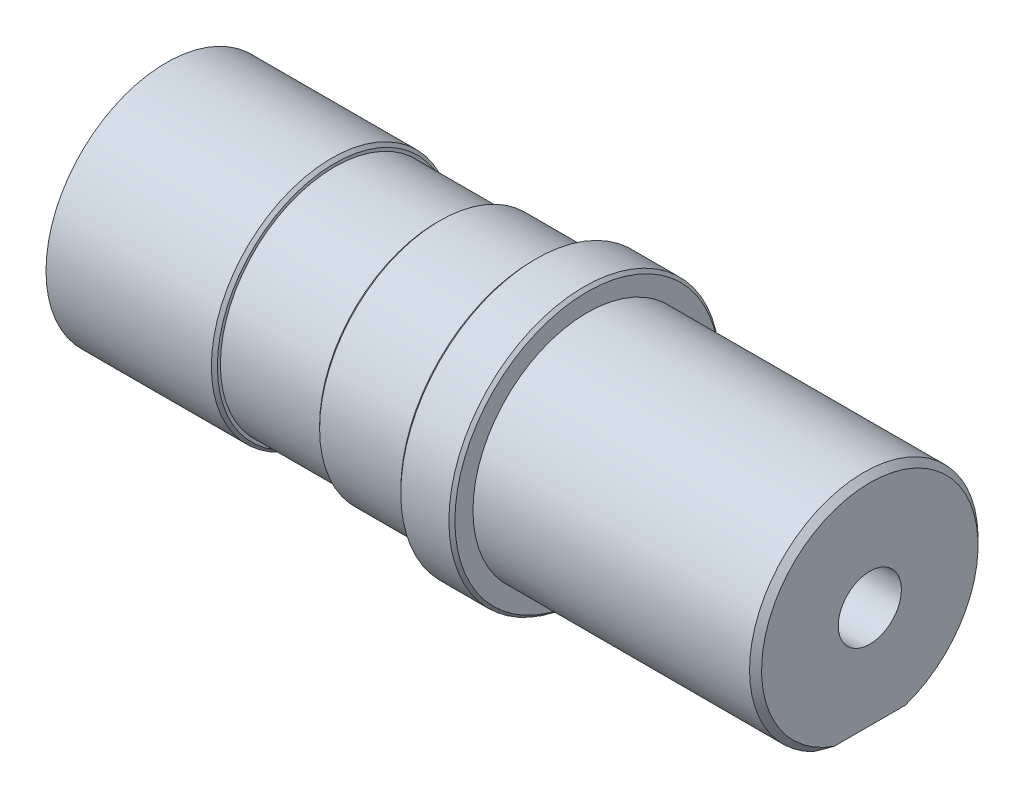
SolidWorks part; units mm, degrees
ref_plane "前视基准面" through (0, 0, 0) normal (0, 0, 1) x (1, 0, 0)
ref_plane "上视基准面" through (0, 0, 0) normal (0, 1, 0) x (1, 0, 0)
ref_plane "右视基准面" through (0, 0, 0) normal (1, 0, 0) x (0, 0, -1)
sketch "草图1" plane through (0, 0, 0) normal (0, 0, 1) x (1, 0, 0)
  line L1 (2043.9736, 794.7901) -> (2043.9736, 776.7901)
  line L2 (1954.9736, 796.2901) -> (1954.9736, 795.7901)
  line L3 (1971.9736, 796.2901) -> (1972.4736, 796.7901)
  line L4 (1996.4736, 799.2901) -> (1988.4736, 799.2901)
  line L5 (1987.9736, 796.7901) -> (1972.4736, 796.7901)
  line L6 (1954.4736, 796.7901) -> (1926.9736, 796.7901)
  line L7 (2042.9736, 795.7901) -> (1996.9736, 795.7901)
  line L8 (1971.9736, 795.7901) -> (1954.9736, 795.7901)
  line L9 (1996.9736, 798.7901) -> (1996.9736, 795.7901)
  line L10 (1971.9736, 796.2901) -> (1971.9736, 795.7901)
  line L11 (1987.9736, 798.7901) -> (1988.4736, 799.2901)
  line L12 (1987.9736, 798.7901) -> (1987.9736, 796.7901)
  line L14 (1954.9736, 796.2901) -> (1954.4736, 796.7901)
  line L16 (1926.9736, 776.7901) -> (2043.9736, 776.7901)
  line L17 (1926.9736, 776.7901) -> (2039.9736, 776.7901) construction
  line L18 (1926.9736, 776.7901) -> (1926.9736, 796.7901)
  line L23 (2042.9736, 795.7901) -> (2043.9736, 794.7901)
  line L26 (2046.9736, 776.7901) -> (2063.4038, 776.7901) construction
  line L27 (1996.4736, 799.2901) -> (1996.9736, 798.7901)
revolve "旋转1" add sketch "草图1" angle 360 about L17
sketch "草图3" plane through (0, 0, 0) normal (0, 0, 1) x (1, 0, 0)
  line L1 (1925.9736, 796.7901) -> (1926.9736, 796.7901)
  line L2 (1926.9736, 796.7901) -> (1926.9736, 795.7901)
  line L3 (1926.9736, 795.7901) -> (1925.9736, 796.7901)
  line L7 (1926.9736, 796.7901) -> (1926.9736, 756.7901) construction
  dimension "D1" = 1
  dimension "D2" = 1
  dimension "D3" = 0
sketch "草图4" plane through (1926.9736, 0, 0) normal (-1, 0, 0) x (0, 0, 1)
  circle A1 centre (0, 776.7901) radius 20 construction
  circle A2 centre (0, 776.7901) radius 20
curve "螺旋线/涡状线1" pitch 1.5 height 15 turns 10
sketch "草图5" plane through (2043.9736, 0, 0) normal (1, 0, 0) x (0, 0, -1)
  line L0 (-8.4853, 759.7901) -> (8.4853, 759.7901)
  arc A2 (-8.4853, 759.7901) -> (8.4853, 759.7901) centre (0, 776.7901) ccw
extrude "切除-拉伸1" cut sketch "草图5" against normal blind 41
hole_wizard "M12x1.5 螺纹孔1" positions "草图7" profile "草图6" tap size "M12x1.5" standard "ISO"
sketch "草图7" plane through (2043.9736, 16.946, 3.006) normal (1, 0, 0) x (0, 0, -1)
  point P1 (3.006, 759.8441)
  dimension "D1" = 0
sketch "草图6" plane through (2043.9736, 776.7901, 0) normal (0, 1, 0) x (0, 0, -1)
  line L0 (0, 0) -> (0, 31.6545)
  line L1 (0, 31.6545) -> (5.25, 28.5)
  line L2 (5.25, 28.5) -> (5.25, 0)
  line L5 (5.25, 0) -> (0, 0)
  line L10 (0, 31.6545) -> (-5.25, 28.5) construction
  line L11 (0, -6.35) -> (0, 107.95) construction
  dimension "螺纹孔钻头直径" = 10.5
  dimension "螺纹孔钻头深度" = 28.5
  dimension "导头角度" = 118
cosmetic thread "孔螺蚊线1" parameters "D1"=24, "D2"=12
sketch "草图8" plane through (0, 759.7901, 0) normal (0, -1, 0) x (1, 0, 0)
  line L0 (1954.4736, 0) -> (1926.9736, 0) construction
  line L1 (1937.9736, 3.25) -> (1926.9736, 3.25)
  line L2 (1937.9736, -3.25) -> (1926.9736, -3.25)
  line L5 (1926.9736, 20) -> (1926.9736, -20) construction
  line L6 (1926.9736, 3.25) -> (1926.9736, -3.25)
  arc A0 (1937.9736, -3.25) -> (1937.9736, 3.25) centre (1937.9736, 0) ccw
  dimension "D1" = 6.5
extrude "切除-拉伸2" cut sketch "草图8" along normal blind 5
